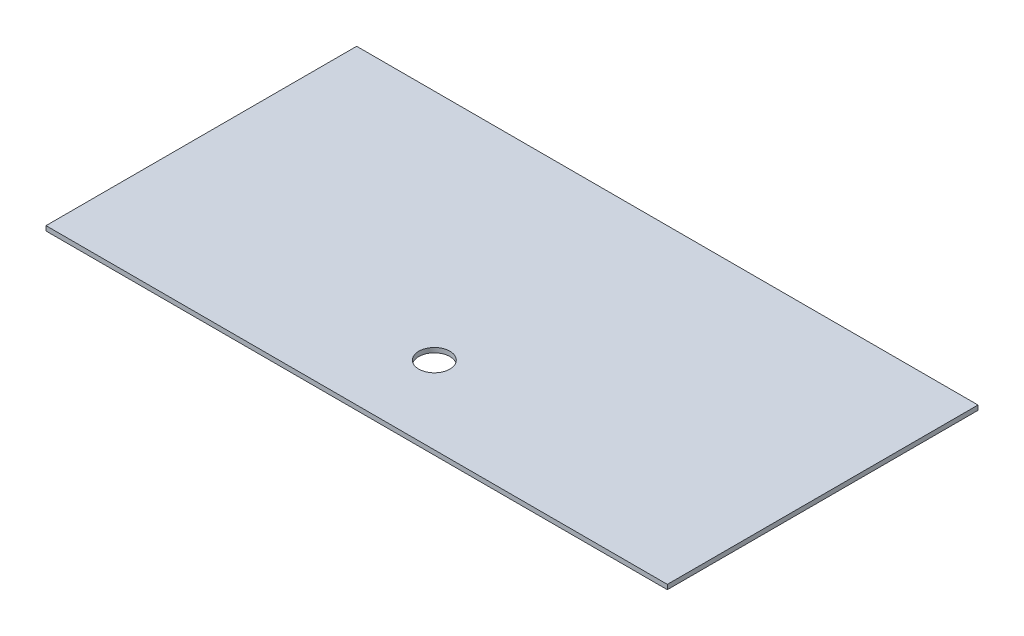
SolidWorks part; units mm, degrees
material "Beech"
ref_plane "Front Plane" through (0, 0, 0) normal (0, 0, 1) x (1, 0, 0)
ref_plane "Top Plane" through (0, 0, 0) normal (0, 1, 0) x (1, 0, 0)
ref_plane "Right Plane" through (0, 0, 0) normal (1, 0, 0) x (0, 0, -1)
sketch "Sketch1" plane through (0, 0, 0) normal (0, 1, 0) x (1, 0, 0)
  line L1 (-1200, -600) -> (1200, -600)
  line L2 (-1200, -600) -> (-1200, 600)
  line L3 (-1200, 600) -> (1200, 600)
  line L4 (1200, -600) -> (1200, 600)
  line L5 (-1200, -600) -> (1200, 600) construction
  line L6 (-1200, 600) -> (1200, -600) construction
  circle A0 centre (0, -300) radius 60
  point P0 (0, 0)
  dimension "D3" = 120
  dimension "D4" = 300
  dimension "D5" = 1200
  dimension "D1" = 2400
  dimension "D2" = 1200
extrude "Boss-Extrude1" add sketch "Sketch1" along normal blind 18
